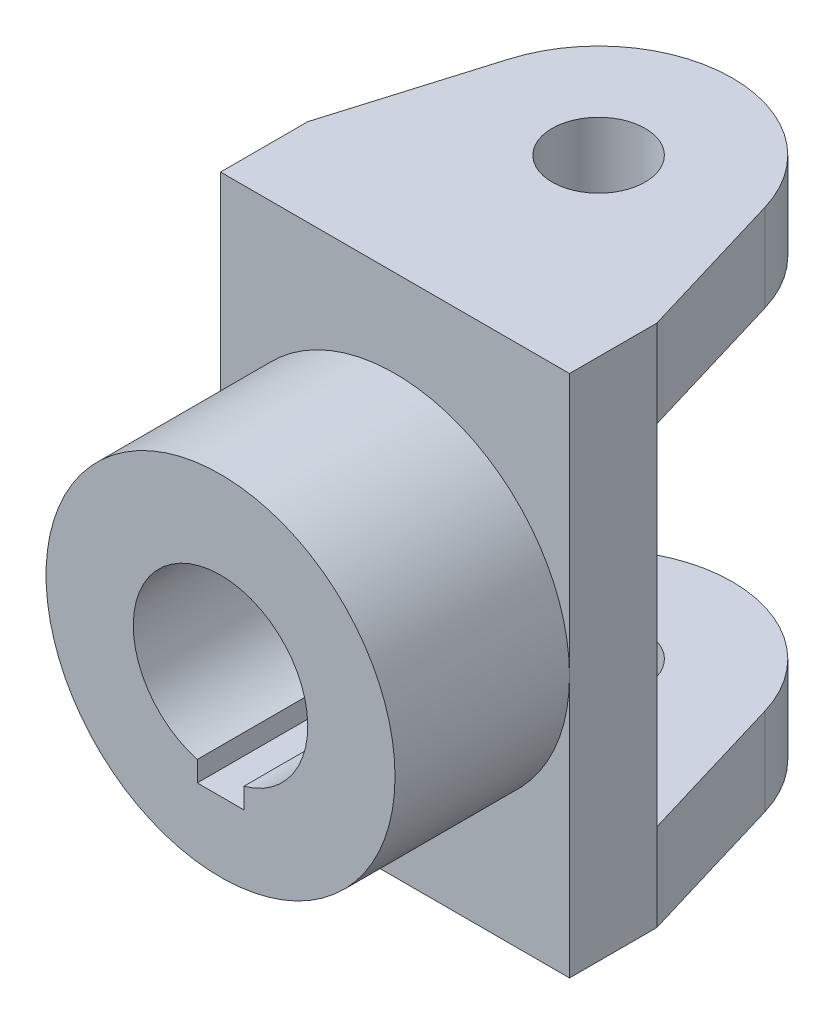
SolidWorks part; units mm, degrees
ref_plane "Front Plane" through (0, 0, 0) normal (0, 0, 1) x (1, 0, 0)
ref_plane "Top Plane" through (0, 0, 0) normal (0, 1, 0) x (1, 0, 0)
ref_plane "Right Plane" through (0, 0, 0) normal (1, 0, 0) x (0, 0, -1)
sketch "Sketch1" plane through (0, 0, 0) normal (0, 0, 1) x (1, 0, 0)
  line L0 (0, 0) -> (0, 51.478) construction
  line L2 (-4, -14.4568) -> (-4, -17.9568)
  line L3 (-4, -17.9568) -> (4, -17.9568)
  line L4 (4, -14.4568) -> (4, -17.9568)
  circle A0 centre (0, 0) radius 30
  arc A1 (4, -14.4568) -> (-4, -14.4568) centre (0, 0) ccw
  dimension "D1" = 60
  dimension "D2" = 30
  dimension "D3" = 8
  dimension "D4" = 3.5
extrude "Boss-Extrude1" add sketch "Sketch1" against normal blind 30
sketch "Sketch2" plane through (0, 0, -30) normal (0, 0, -1) x (-1, 0, 0)
  line L1 (30, 45) -> (-30, 45)
  line L2 (30, 45) -> (30, -45)
  line L3 (30, -45) -> (-30, -45)
  line L4 (-30, 45) -> (-30, -45)
  line L5 (30, 45) -> (-30, -45) construction
  line L6 (30, -45) -> (-30, 45) construction
  point P0 (0, 0)
  dimension "D1" = 90
  dimension "D2" = 60
extrude "Boss-Extrude2" add sketch "Sketch2" along normal blind 15
sketch "Sketch3" plane through (0, 45, 0) normal (0, 1, 0) x (1, 0, 0)
  line L0 (-30, 30) -> (30, 30) construction
  line L1 (22.0329, 71.5993) -> (30, 45)
  line L2 (30, 45) -> (30, 30)
  line L3 (30, 30) -> (-30, 30)
  line L4 (-30, 30) -> (-30, 45)
  line L5 (-30, 45) -> (-22.0329, 71.5993)
  arc A0 (22.0329, 71.5993) -> (-22.0329, 71.5993) centre (0, 65) ccw
  circle A1 centre (0, 65) radius 8
  dimension "D1" = 46
  dimension "D2" = 16
  dimension "D3" = 35
extrude "Boss-Extrude3" add sketch "Sketch3" against normal blind 15
mirror "Mirror1" about plane through (0, 0, 0) normal (0, 1, 0) of "Boss-Extrude3"
